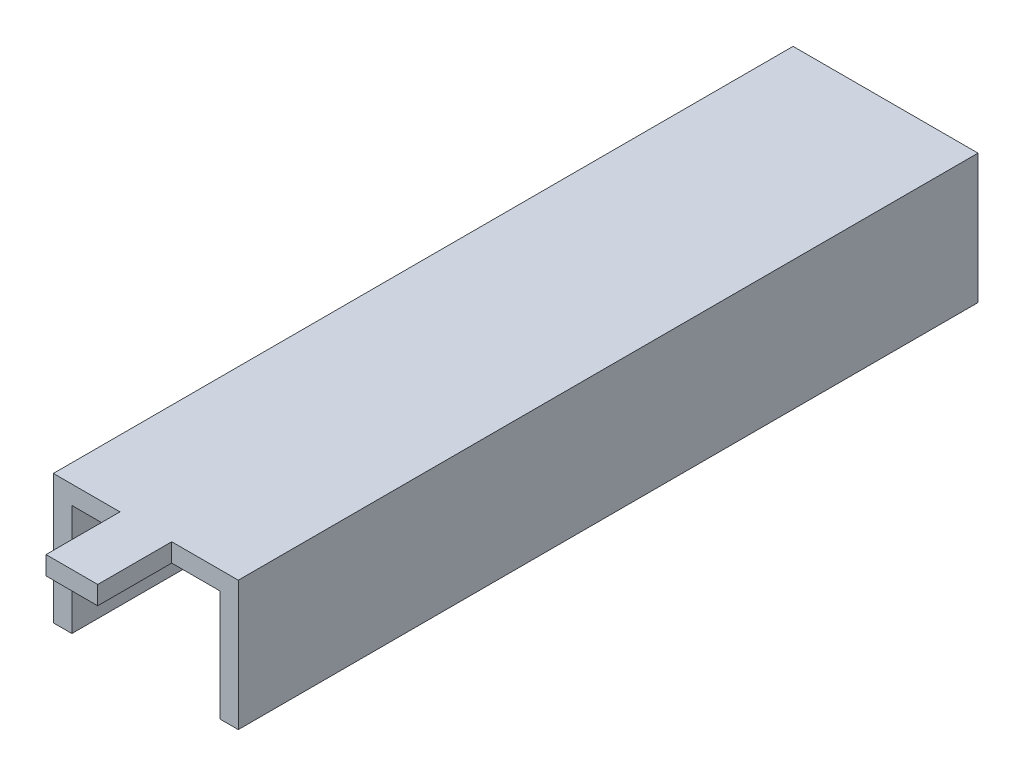
SolidWorks part; units mm, degrees
ref_plane "Front Plane" through (0, 0, 0) normal (0, 0, 1) x (1, 0, 0)
ref_plane "Top Plane" through (0, 0, 0) normal (0, 1, 0) x (1, 0, 0)
ref_plane "Right Plane" through (0, 0, 0) normal (1, 0, 0) x (0, 0, -1)
sketch "Sketch1" plane through (0, 0, 0) normal (0, 0, 1) x (1, 0, 0)
  line L1 (0, 0) -> (6.35, 0)
  line L2 (0, 0) -> (0, 44.45)
  line L3 (0, 44.45) -> (6.35, 44.45)
  line L4 (6.35, 0) -> (6.35, 38.1)
  line L5 (6.35, 44.45) -> (57.15, 44.45)
  line L7 (6.35, 38.1) -> (57.15, 38.1)
  line L9 (57.15, 44.45) -> (63.5, 44.45)
  line L10 (57.15, 38.1) -> (57.15, 0)
  line L11 (57.15, 0) -> (63.5, 0)
  line L12 (63.5, 44.45) -> (63.5, 0)
  dimension "D1" = 63.5
  dimension "D2" = 44.45
  dimension "D3" = 6.35
  dimension "D4" = 6.35
extrude "Boss-Extrude1" add sketch "Sketch1" along normal blind 254
sketch "Sketch2" plane through (0, 0, 254) normal (0, 0, 1) x (1, 0, 0)
  line L0 (6.35, 38.1) -> (57.15, 38.1) construction
  line L1 (22.8704, 38.1) -> (40.6296, 38.1)
  line L2 (22.8704, 38.1) -> (22.8704, 44.45)
  line L3 (22.8704, 44.45) -> (40.6296, 44.45)
  line L4 (40.6296, 38.1) -> (40.6296, 44.45)
  line L5 (63.5, 44.45) -> (0, 44.45) construction
  line L6 (22.8704, 41.275) -> (0, 41.275) construction
  line L7 (0, 44.45) -> (0, 0) construction
  line L8 (0, 41.275) -> (40.6296, 41.275) construction
  line L9 (40.6296, 41.275) -> (63.5, 41.275) construction
  line L10 (63.5, 0) -> (63.5, 44.45) construction
extrude "Boss-Extrude2" add sketch "Sketch2" along normal blind 25.4
